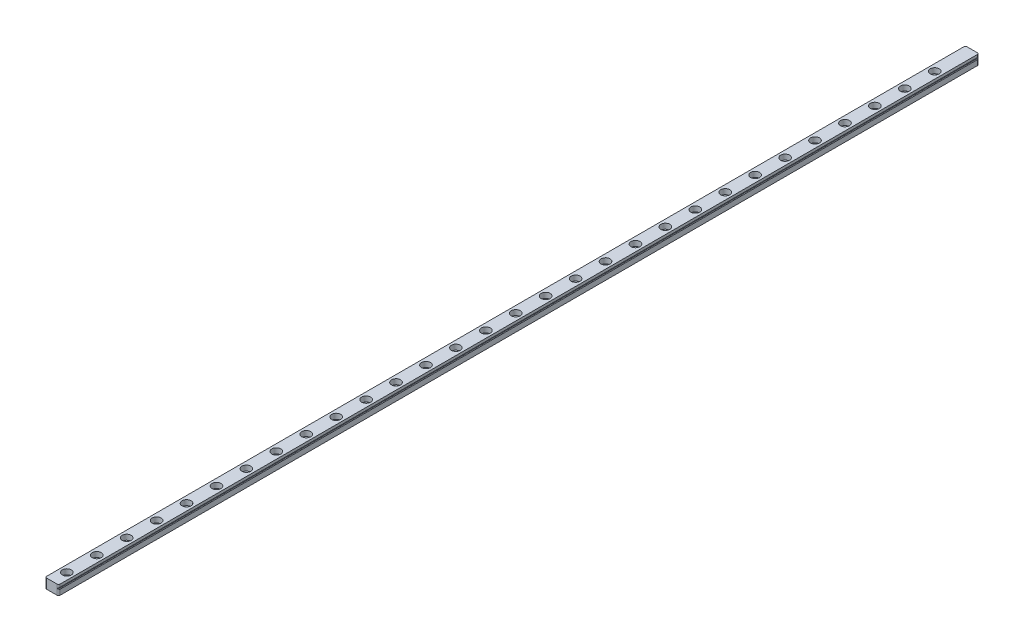
SolidWorks part; units mm, degrees
material "镀铬不锈钢"
ref_plane "前视基准面" through (0, 0, 0) normal (0, 0, 1) x (1, 0, 0)
ref_plane "上视基准面" through (0, 0, 0) normal (0, 1, 0) x (1, 0, 0)
ref_plane "右视基准面" through (0, 0, 0) normal (1, 0, 0) x (0, 0, -1)
sketch "草图2" plane through (0, 0, 0) normal (0, 0, 1) x (1, 0, 0)
  line L0 (0, 0) -> (9, 0)
  line L1 (4.5, 0) -> (4.5, 7.3268) construction
  line L2 (9, 0) -> (9, 3.5)
  line L3 (9, 3.5) -> (8.6464, 3.8536)
  line L4 (8.6464, 3.8536) -> (8.1464, 3.8536)
  line L5 (8.1464, 3.8536) -> (8.1464, 4.3536)
  line L6 (8.1464, 4.3536) -> (8.6464, 4.3536)
  line L7 (8.6464, 4.3536) -> (9, 4.7071)
  line L8 (9, 4.7071) -> (9, 6.5)
  line L9 (9, 6.5) -> (0, 6.5)
  line L10 (0, 4.7071) -> (0, 6.5)
  line L11 (0.3536, 4.3536) -> (0, 4.7071)
  line L12 (0.8536, 4.3536) -> (0.3536, 4.3536)
  line L13 (0.8536, 3.8536) -> (0.8536, 4.3536)
  line L14 (0.3536, 3.8536) -> (0.8536, 3.8536)
  line L15 (0, 3.5) -> (0.3536, 3.8536)
  line L16 (0, 0) -> (0, 3.5)
  point P14 (4.5, 6.5)
  dimension "D1" = 9
  dimension "D2" = 3.5
  dimension "D3" = 135
  dimension "D4" = 0.5
  dimension "D5" = 0.5
  dimension "D6" = 0.5
  dimension "D7" = 0.5
  dimension "D8" = 6.5
extrude "凸台-拉伸2" add sketch "草图2" against normal blind 615
sketch "草图3" plane through (0, 6.5, 0) normal (0, 1, 0) x (1, 0, 0)
  line L0 (9, 0) -> (0, 0) construction
  circle A0 centre (4.5, 10) radius 3
  point P2 (4.5, 0)
  dimension "D1" = 6
  dimension "D2" = 10
  dimension "D3" = 4.5
extrude "切除-拉伸1" cut sketch "草图3" against normal blind 3.5
sketch "草图4" plane through (0, 3, 0) normal (0, 1, 0) x (1, 0, 0)
  circle A0 centre (4.5, 10) radius 1.75
  dimension "D1" = 3.5
extrude "切除-拉伸2" cut sketch "草图4" against normal up to surface (3 mm away) up to face at (4.5, 0, -307.5)
pattern_linear "阵列(线性)1" count 30 spacing 20 along (0, 0, -1) of "切除-拉伸1", "切除-拉伸2"
fillet "圆角1" radius 1 4 edges at (9, 1.75, -615) (0, 1.75, -615) (9, 1.75, 0) (0, 1.75, 0)
equation "\"导轨长度\"= 615"
equation "\"D1@凸台-拉伸2\"=\"导轨长度\""
equation "\"D1@阵列(线性)1\"=int( \"导轨长度\"/20)"
